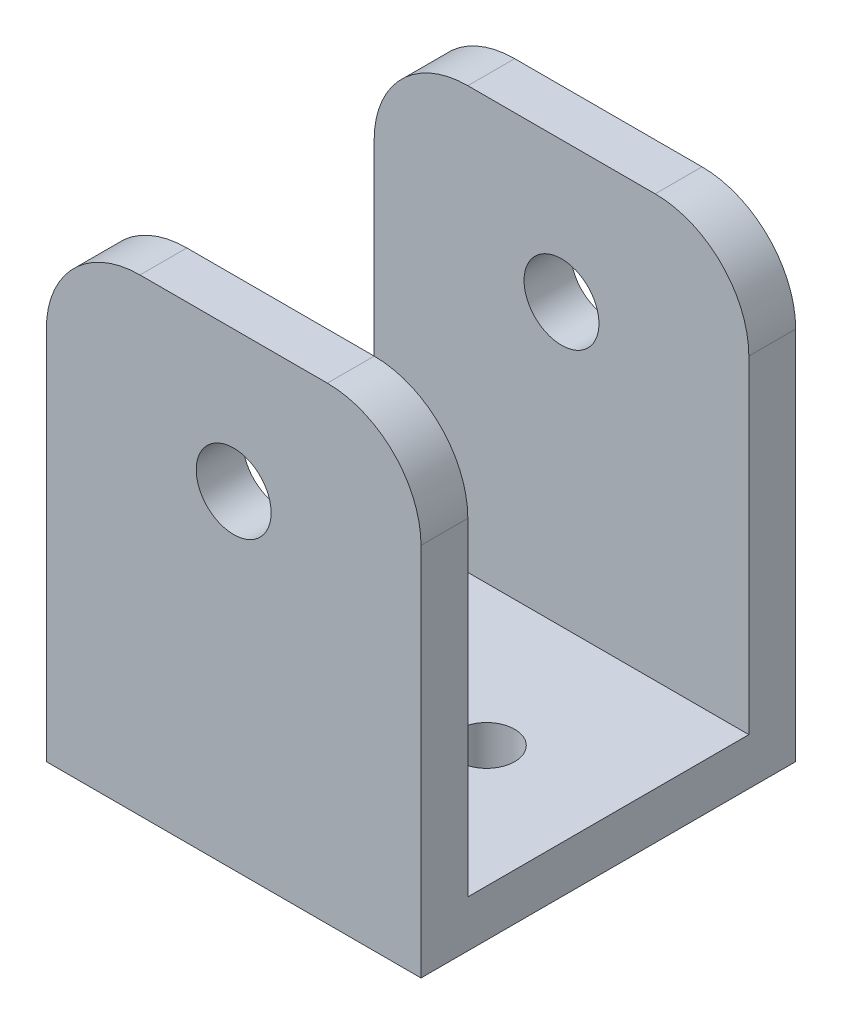
SolidWorks part; units mm, degrees
ref_plane "Front Plane" through (0, 0, 0) normal (0, 0, 1) x (1, 0, 0)
ref_plane "Top Plane" through (0, 0, 0) normal (0, 1, 0) x (1, 0, 0)
ref_plane "Right Plane" through (0, 0, 0) normal (1, 0, 0) x (0, 0, -1)
sketch "Sketch1" plane through (0, 0, 0) normal (0, 0, 1) x (1, 0, 0)
  line L0 (0, 15) -> (0, -50.674) construction
  line L1 (-20, -35) -> (20, -35)
  line L2 (20, -35) -> (20, 5)
  line L3 (-20, -35) -> (-20, 5)
  line L4 (10, 15) -> (-10, 15)
  arc A0 (-20, 5) -> (-10, 15) centre (-10, 5) cw
  circle A1 centre (0, 0) radius 4
  arc A2 (20, 5) -> (10, 15) centre (10, 5) ccw
  point P1 (0, -35)
  point P10 (-20, 20)
  point P15 (-20, 20)
  point P16 (-20, 20)
  dimension "D1" = 55
  dimension "D2" = 35
  dimension "D5" = 8
  dimension "D3" = 10
  dimension "D4" = 40
extrude "Boss-Extrude4" add sketch "Sketch1" along normal blind 5
sketch "Sketch4" plane through (0, 0, 0) normal (0, 0, -1) x (-1, 0, 0)
  line L1 (-20, -30) -> (20, -30)
  line L2 (-20, -30) -> (-20, -35)
  line L3 (-20, -35) -> (20, -35)
  line L4 (20, -30) -> (20, -35)
  line L5 (-20, -30) -> (20, -35) construction
  line L6 (-20, -35) -> (20, -30) construction
  point P0 (0, -32.5)
  dimension "D1" = 5
  dimension "D2" = 40
extrude "Boss-Extrude5" add sketch "Sketch4" along normal blind 30
sketch "Sketch5" plane through (0, 0, -30) normal (0, 0, -1) x (-1, 0, 0)
  line L0 (-20, -35) -> (20, -35)
  line L1 (20, -35) -> (20, -30)
  line L2 (20, -30) -> (-20, -30)
  line L3 (-20, -30) -> (-20, -35)
  line L4 (-20, -30) -> (-20, 0)
  line L5 (20, -30) -> (20, 5)
  line L6 (20, 0) -> (20, -30)
  line L7 (10, 15) -> (-10, 15)
  line L8 (-20, 5) -> (-20, -30)
  arc A1 (-10, 15) -> (-20, 5) centre (-10, 5) ccw
  circle A2 centre (0, 0) radius 4
  arc A3 (20, 5) -> (10, 15) centre (10, 5) ccw
  dimension "D1" = 10
  dimension "D2" = 8
  dimension "D3" = 30
extrude "Boss-Extrude6" add sketch "Sketch5" along normal blind 5
sketch "Sketch7" plane through (0, -30, 0) normal (0, 1, 0) x (1, 0, 0)
  line L0 (-20, 0) -> (20, 0) construction
  line L4 (-20, 30) -> (-20, 0) construction
  circle A0 centre (-7, 15) radius 3
  circle A1 centre (7, 15) radius 3
  dimension "D1" = 6
  dimension "D2" = 6
  dimension "D3" = 15
  dimension "D4" = 14
  dimension "D5" = 13
  dimension "D6" = 15
extrude "Cut-Extrude1" cut sketch "Sketch7" against normal blind 15
